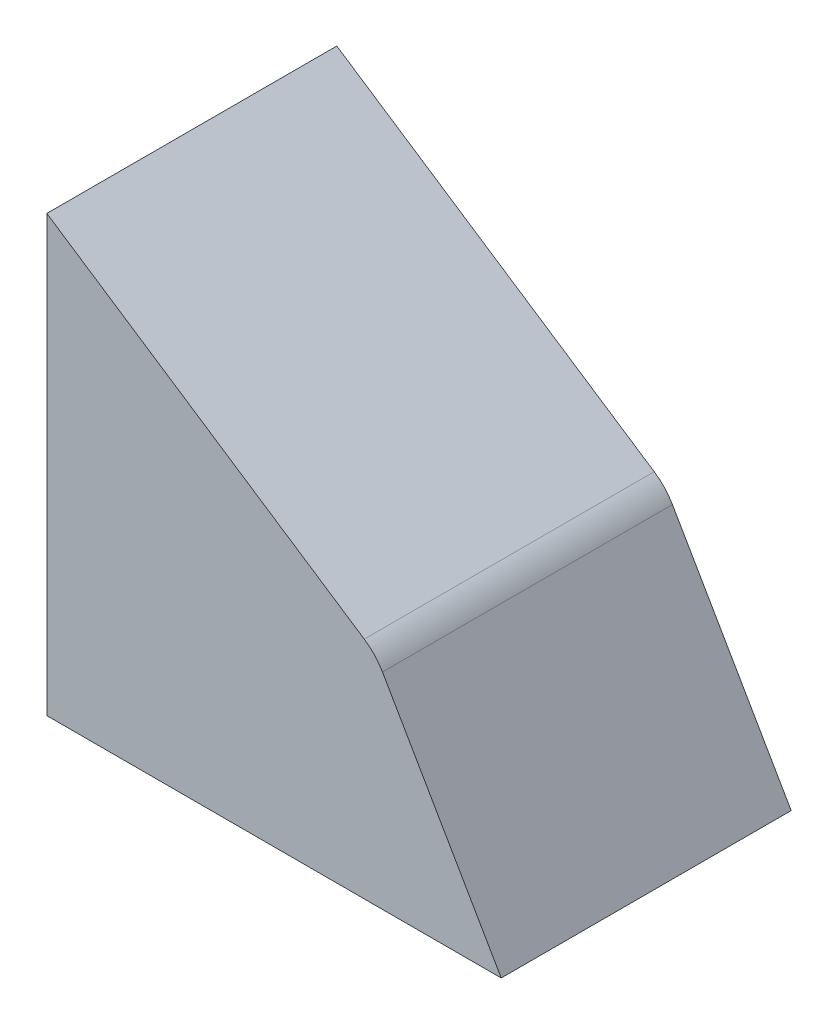
SolidWorks part; units mm, degrees
ref_plane "Front Plane" through (0, 0, 0) normal (0, 0, 1) x (1, 0, 0)
ref_plane "Top Plane" through (0, 0, 0) normal (0, 1, 0) x (1, 0, 0)
ref_plane "Right Plane" through (0, 0, 0) normal (1, 0, 0) x (0, 0, -1)
sketch "Sketch2" plane through (0, 0, 0) normal (0, 0, 1) x (1, 0, 0)
  line L0 (-8.6603, 0) -> (-12.9904, 7.5) construction
  line L1 (8.6603, 0) -> (4.3301, 7.5) construction
  line L2 (4.3301, 7.5) -> (-4.3301, 7.5) construction
  line L3 (-4.3301, 7.5) -> (-8.6603, 0) construction
  line L4 (-8.6603, 0) -> (-4.3301, -7.5)
  line L5 (-4.3301, -7.5) -> (4.3301, -7.5) construction
  line L6 (4.3301, -7.5) -> (8.6603, 0) construction
  line L7 (-12.9904, 7.5) -> (-20.0001, 7.5) construction
  line L8 (-20.0001, 7.5) -> (-20.0001, -7.5)
  line L9 (-20.0001, -7.5) -> (-4.3301, -7.5)
  line L10 (-8.6603, 0) -> (-20.0001, 7.5)
  circle A0 centre (0, 0) radius 7.5 construction
  dimension "D1" = 15
  dimension "D2" = 15.67
  dimension "D3" = 15
extrude "Boss-Extrude1" add sketch "Sketch2" along normal blind 10
fillet "Fillet1" radius 2 1 edges at (-8.6603, 0, 5)
